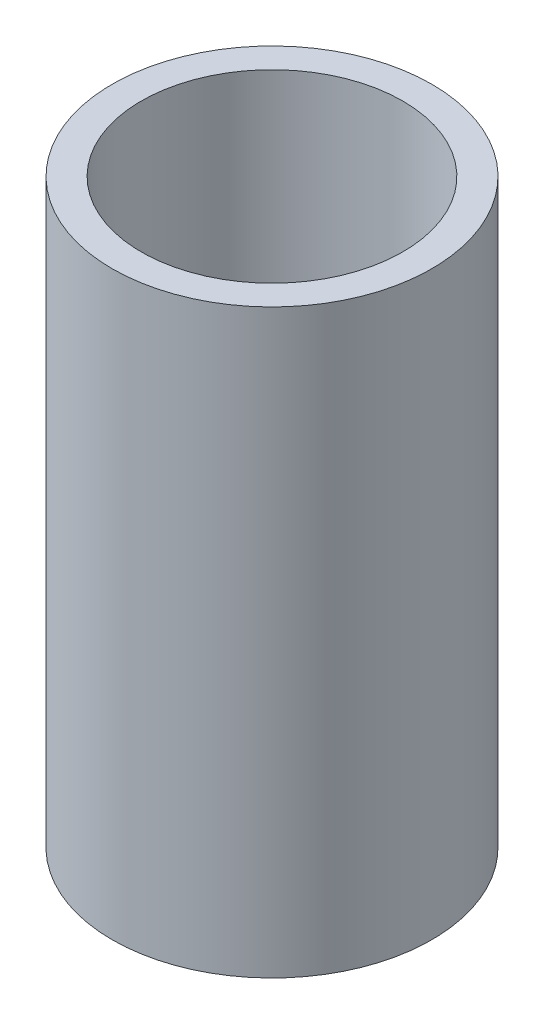
SolidWorks part; units mm, degrees
ref_plane "Спереди" through (0, 0, 0) normal (0, 0, 1) x (1, 0, 0)
ref_plane "Сверху" through (0, 0, 0) normal (0, 1, 0) x (1, 0, 0)
ref_plane "Справа" through (0, 0, 0) normal (1, 0, 0) x (0, 0, -1)
sketch "Эскиз1" plane through (0, 0, 0) normal (0, 0, 1) x (1, 0, 0)
  line L0 (0, -110.6031) -> (0, 130.0787) construction
  line L1 (45, 100) -> (55, 100)
  line L2 (45, 100) -> (45, -100)
  line L3 (45, -100) -> (55, -100)
  line L4 (55, 100) -> (55, -100)
  point P4 (45, 0)
  dimension "D1" = 10
  dimension "D2" = 200
  dimension "D3" = 45
revolve "Повернуть1" add sketch "Эскиз1" angle 360 about L0
ref_plane "Плоскость1" through (-55, 0, 0) normal (-1, 0, 0) x (0, 0, 1)
sketch "Эскиз2" plane through (-55, 0, 0) normal (-1, 0, 0) x (0, 0, 1)
  circle A0 centre (0, 0) radius 25
  circle A1 centre (70, 0) radius 25
  circle A2 centre (140, 0) radius 25
  circle A3 centre (210, 0) radius 25
  dimension "D1" = 50
  dimension "D2" = 4
